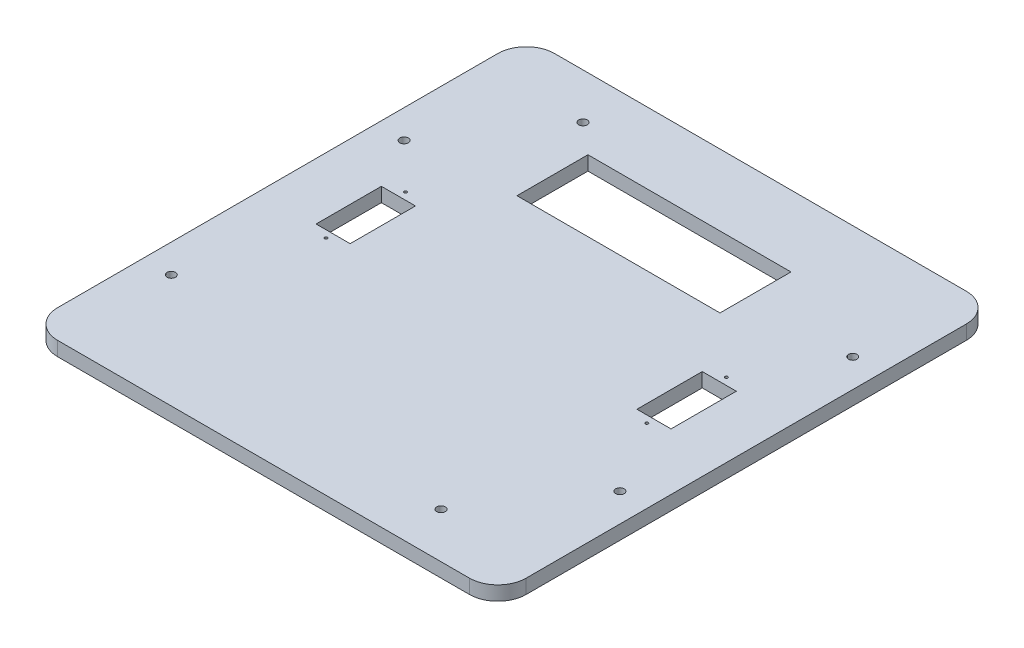
SolidWorks part; units mm, degrees
material "Acrílico (médio-alto impacto)"
ref_plane "Plano frontal" through (0, 0, 0) normal (0, 0, 1) x (1, 0, 0)
ref_plane "Plano superior" through (0, 0, 0) normal (0, 1, 0) x (1, 0, 0)
ref_plane "Plano direito" through (0, 0, 0) normal (1, 0, 0) x (0, 0, -1)
sketch "Esboço1" plane through (0, 0, 0) normal (0, 1, 0) x (1, 0, 0)
  line L1 (-25.4636, 142.2644) -> (119.5364, 142.2644)
  line L2 (-35.4636, 132.2644) -> (-35.4636, -22.7356)
  line L3 (-25.4636, -32.7356) -> (119.5364, -32.7356)
  line L4 (129.5364, 132.2644) -> (129.5364, -22.7356)
  arc A0 (119.5364, 142.2644) -> (129.5364, 132.2644) centre (119.5364, 132.2644) cw
  arc A1 (119.5364, -32.7356) -> (129.5364, -22.7356) centre (119.5364, -22.7356) ccw
  arc A2 (-35.4636, -22.7356) -> (-25.4636, -32.7356) centre (-25.4636, -22.7356) ccw
  arc A3 (-25.4636, 142.2644) -> (-35.4636, 132.2644) centre (-25.4636, 132.2644) ccw
  arc A4 (119.5364, 142.2644) -> (129.5364, 132.2644) centre (119.5364, 132.2644) cw
  dimension "D1" = 10
  dimension "D2" = 10
extrude "Ressalto-extrusão1" add sketch "Esboço1" along normal blind 5 contours L1 A3 L2 A2 L3 A1 L4 A0
sketch "Esboço2" plane through (0, 5, 0) normal (0, 1, 0) x (1, 0, 0)
  line L0 (-35.4636, 132.2644) -> (-35.4636, -22.7356) construction
  line L1 (-25.4636, -32.7356) -> (119.5364, -32.7356) construction
  line L2 (129.5364, 132.2644) -> (129.5364, -22.7356) construction
  line L3 (-25.4636, 142.2644) -> (119.5364, 142.2644) construction
  circle A0 centre (-25.4636, 7.2644) radius 1.5
  circle A1 centre (0.5364, 126.2644) radius 1.5
  circle A2 centre (119.5364, 102.2644) radius 1.5
  circle A3 centre (93.5364, -16.7356) radius 1.5
  dimension "D1" = 10
  dimension "D2" = 40
  dimension "D3" = 10
  dimension "D4" = 40
  dimension "D5" = 16
  dimension "D6" = 36
  dimension "D7" = 36
  dimension "D8" = 16
  dimension "D9" = 3
  dimension "D10" = 3
  dimension "D11" = 3
  dimension "D12" = 3
extrude "Corte-extrusão1" cut sketch "Esboço2" against normal blind 5
sketch "Esboço4" plane through (0, 5, 0) normal (0, 1, 0) x (1, 0, 0)
  line L0 (-35.4636, 132.2644) -> (-35.4636, -22.7356) construction
  line L1 (-25.4636, -32.7356) -> (119.5364, -32.7356) construction
  line L2 (-25.4636, 142.2644) -> (119.5364, 142.2644) construction
  line L3 (129.5364, 132.2644) -> (129.5364, -22.7356) construction
  line L5 (-15.4636, 48.2644) -> (-3.4636, 48.2644)
  line L6 (-15.4636, 48.2644) -> (-15.4636, 71.2644)
  line L7 (-15.4636, 71.2644) -> (-3.4636, 71.2644)
  line L8 (-3.4636, 48.2644) -> (-3.4636, 71.2644)
  line L9 (109.5364, 48.2644) -> (97.5364, 48.2644)
  line L10 (109.5364, 48.2644) -> (109.5364, 71.2644)
  line L11 (109.5364, 71.2644) -> (97.5364, 71.2644)
  line L12 (97.5364, 48.2644) -> (97.5364, 71.2644)
  circle A0 centre (-9.4636, 45.7644) radius 0.5
  circle A1 centre (-9.4636, 73.7644) radius 0.5
  circle A2 centre (103.5364, 45.7644) radius 0.5
  circle A3 centre (103.5364, 73.7644) radius 0.5
  point P24 (129.5364, 54.7644)
  dimension "D1" = 26
  dimension "D2" = 26
  dimension "D3" = 1
  dimension "D4" = 1
  dimension "D5" = 78.5
  dimension "D6" = 68.5
  dimension "D7" = 78.5
  dimension "D8" = 68.5
  dimension "D9" = 1
  dimension "D10" = 1
  dimension "D11" = 26
  dimension "D12" = 26
  dimension "D13" = 28
  dimension "D14" = 2.5
  dimension "D15" = 2.5
  dimension "D16" = 12
  dimension "D17" = 20
  dimension "D18" = 20
  dimension "D19" = 12
  dimension "D20" = 2.5
  dimension "D21" = 2.5
  dimension "D22" = 23
  dimension "D23" = 23
extrude "Corte-extrusão3" cut sketch "Esboço4" against normal through all
sketch "Esboço5" plane through (0, 5, 0) normal (0, 1, 0) x (1, 0, 0)
  line L0 (-25.4636, 142.2644) -> (119.5364, 142.2644) construction
  line L1 (11.2864, 92.2644) -> (82.7864, 92.2644)
  line L2 (11.2864, 92.2644) -> (11.2864, 117.2644)
  line L3 (11.2864, 117.2644) -> (82.7864, 117.2644)
  line L4 (82.7864, 92.2644) -> (82.7864, 117.2644)
  line L7 (-35.4636, 132.2644) -> (-35.4636, -22.7356) construction
  line L11 (129.5364, 132.2644) -> (129.5364, -22.7356) construction
  line L12 (-25.4636, -32.7356) -> (119.5364, -32.7356) construction
  circle A0 centre (-25.4636, 89.2644) radius 1.5
  circle A1 centre (119.5364, 20.2644) radius 1.5
  dimension "D5" = 3
  dimension "D6" = 53
  dimension "D7" = 10
  dimension "D8" = 3
  dimension "D9" = 10
  dimension "D10" = 53
  dimension "D1" = 25
  dimension "D2" = 25
  dimension "D3" = 71.5
  dimension "D4" = 46.75
extrude "Corte-extrusão4" cut sketch "Esboço5" against normal through all
